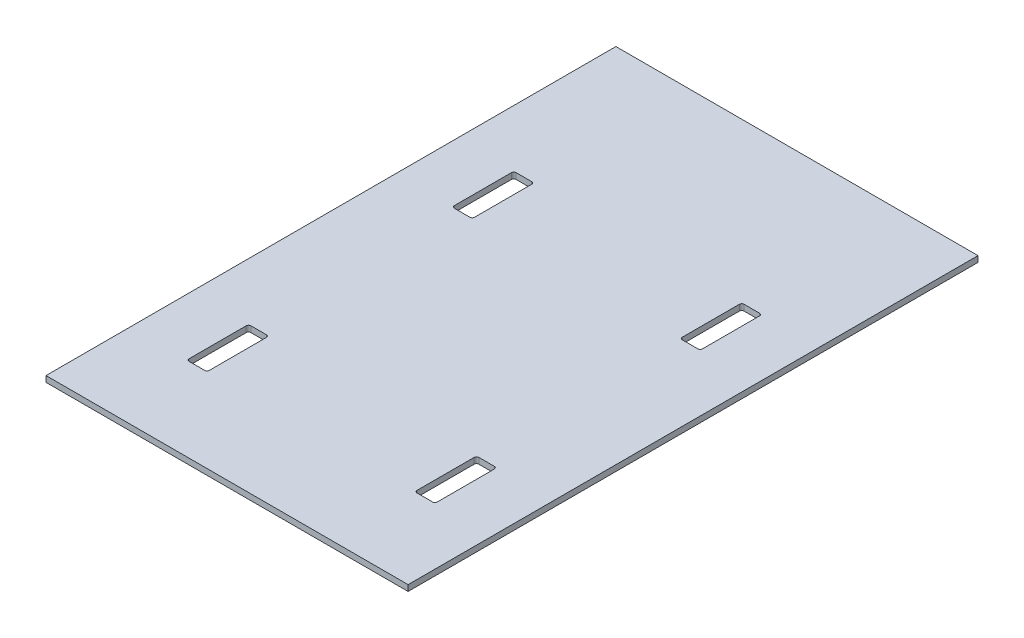
SolidWorks part; units mm, degrees
ref_plane "Front Plane" through (0, 0, 0) normal (0, 0, 1) x (1, 0, 0)
ref_plane "Top Plane" through (0, 0, 0) normal (0, 1, 0) x (1, 0, 0)
ref_plane "Right Plane" through (0, 0, 0) normal (1, 0, 0) x (0, 0, -1)
sketch "Sketch1" plane through (0, 0, 0) normal (0, 1, 0) x (1, 0, 0)
  line L1 (-193.675, -304.8) -> (193.675, -304.8)
  line L2 (-193.675, -304.8) -> (-193.675, 304.8)
  line L3 (-193.675, 304.8) -> (193.675, 304.8)
  line L4 (193.675, -304.8) -> (193.675, 304.8)
  line L5 (0, 304.8) -> (0, -304.8) construction
  line L6 (-193.675, 0) -> (193.675, 0) construction
  point P0 (0, 0)
  dimension "D1" = 387.35
  dimension "D2" = 609.6
extrude "Boss-Extrude1" add sketch "Sketch1" along normal blind 6.35
sketch "Sketch2" plane through (0, 6.35, 0) normal (0, 1, 0) x (1, 0, 0)
  line L0 (0, -1000) -> (0, 49000) construction
  line L6 (111.125, -215.138) -> (132.715, -215.138)
  line L7 (111.125, 68.58) -> (132.715, 68.58)
  line L8 (111.125, 68.58) -> (111.125, 134.62)
  line L9 (111.125, 134.62) -> (132.715, 134.62)
  line L10 (132.715, 68.58) -> (132.715, 134.62)
  line L11 (121.92, 134.62) -> (121.92, 68.58) construction
  line L12 (111.125, 101.6) -> (132.715, 101.6) construction
  line L17 (111.125, -215.138) -> (111.125, -149.098)
  line L18 (111.125, -149.098) -> (132.715, -149.098)
  line L23 (132.715, -215.138) -> (132.715, -149.098)
  line L24 (121.92, -149.098) -> (121.92, -215.138) construction
  line L25 (111.125, -182.118) -> (132.715, -182.118) construction
  line L26 (-121.92, -149.098) -> (-121.92, -215.138) construction
  line L27 (-132.715, -215.138) -> (-132.715, -149.098)
  line L28 (-111.125, -215.138) -> (-111.125, -149.098)
  line L29 (-111.125, -215.138) -> (-132.715, -215.138)
  line L30 (-111.125, -182.118) -> (-132.715, -182.118) construction
  line L31 (-111.125, -149.098) -> (-132.715, -149.098)
  line L32 (-111.125, 101.6) -> (-132.715, 101.6) construction
  line L33 (-121.92, 134.62) -> (-121.92, 68.58) construction
  line L34 (-132.715, 68.58) -> (-132.715, 134.62)
  line L35 (-111.125, 134.62) -> (-132.715, 134.62)
  line L36 (-111.125, 68.58) -> (-111.125, 134.62)
  line L37 (-111.125, 68.58) -> (-132.715, 68.58)
  line L38 (193.675, 304.8) -> (-193.675, 304.8) construction
  point P1 (121.92, -182.118)
  point P4 (121.92, 101.6)
  point P20 (-121.92, -182.118)
  point P29 (-121.92, 101.6)
  dimension "D1" = 66.04
  dimension "D2" = 21.59
  dimension "D3" = 66.04
  dimension "D4" = 283.718
  dimension "D5" = 203.2
  dimension "D6" = 121.92
extrude "Cut-Extrude1" cut sketch "Sketch2" against normal through all
fillet "Fillet1" radius 2.54 16 edges at (-132.715, 3.175, -134.62) (-111.125, 3.175, -134.62) (132.715, 3.175, 215.138) (132.715, 3.175, 149.098) (111.125, 3.175, 149.098) (111.125, 3.175, 215.138) (-111.125, 3.175, 215.138) (-132.715, 3.175, 215.138) (-111.125, 3.175, 149.098) (-132.715, 3.175, 149.098) (132.715, 3.175, -68.58) (111.125, 3.175, -68.58) (132.715, 3.175, -134.62) (111.125, 3.175, -134.62) (-111.125, 3.175, -68.58) (-132.715, 3.175, -68.58)
ref_plane "front_wheel" through (0, 0, -101.6) normal (0, 0, 1) x (1, 0, 0)
ref_plane "back_wheel" through (0, 0, 182.118) normal (0, 0, 1) x (1, 0, 0)
